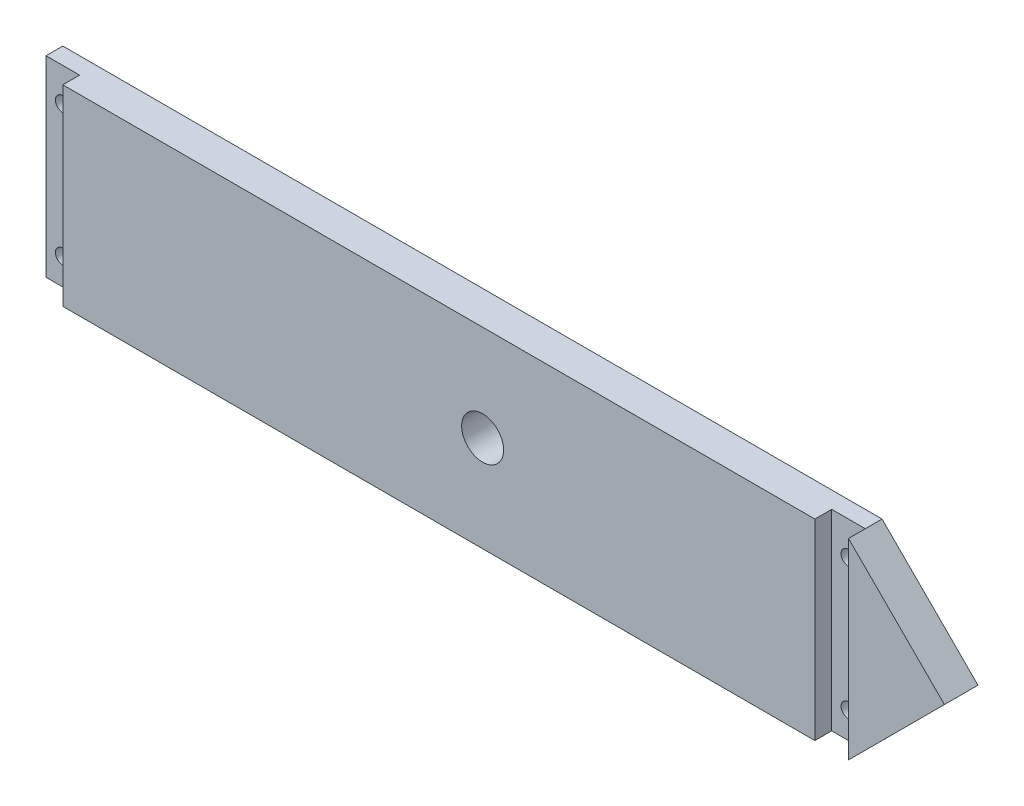
SolidWorks part; units mm, degrees
material "Brass"
ref_plane "Front Plane" through (0, 0, 0) normal (0, 0, 1) x (1, 0, 0)
ref_plane "Top Plane" through (0, 0, 0) normal (0, 1, 0) x (1, 0, 0)
ref_plane "Right Plane" through (0, 0, 0) normal (1, 0, 0) x (0, 0, -1)
sketch "Sketch1" plane through (0, 0, 0) normal (0, 0, 1) x (1, 0, 0)
  line L0 (86.5187, 18.1394) -> (-86.5187, -18.1394) construction
  line L1 (86.5187, 18.1394) -> (-86.5187, 18.1394)
  line L2 (86.5187, 18.1394) -> (86.5187, -18.1394)
  line L3 (86.5187, -18.1394) -> (-86.5187, -18.1394)
  line L4 (-86.5187, 18.1394) -> (-86.5187, -18.1394)
  line L5 (0, 67.5638) -> (0, -55.9908) construction
  line L6 (-104.9725, 0) -> (100.2455, 0) construction
  dimension "sight arm length" = 173.0375
  dimension "D2" = 36.2788
extrude "Extrude2" add sketch "Sketch1" along normal blind 6.35
sketch "Sketch8" plane through (0, 0, 6.35) normal (0, 0, 1) x (1, 0, 0)
  line L0 (-0.7937, -951.8707) -> (-0.7937, 49048.1293) construction
  line L1 (-80.1687, -1000.1415) -> (-80.1687, 48999.8585) construction
  line L2 (62.0306, -999.8068) -> (62.0306, 49000.1932) construction
  line L3 (68.3806, -999.1373) -> (68.3806, 49000.8627) construction
  line L5 (-86.5187, 18.1394) -> (-80.1687, 18.1394)
  line L6 (-80.1687, 18.1394) -> (-80.1687, -18.1394)
  line L8 (-80.1687, -18.1394) -> (-86.5187, -18.1394)
  line L9 (-86.5187, -18.1394) -> (-86.5187, 18.1394)
  line L10 (62.0306, 18.1394) -> (68.3806, 18.1394)
  line L11 (86.5187, 18.1394) -> (-86.5187, 18.1394) construction
  line L12 (68.3806, 18.1394) -> (68.3806, -18.1394)
  line L13 (68.3806, -18.1394) -> (62.0306, -18.1394)
  line L14 (-86.5187, -18.1394) -> (86.5187, -18.1394) construction
  line L15 (62.0306, -18.1394) -> (62.0306, 18.1394)
  line L17 (86.5187, -18.1394) -> (86.5187, 18.1394) construction
  dimension "D1" = 6.35
  dimension "D2" = 6.35
  dimension "D3" = 18.1381
  dimension "D4" = 173.0375
  dimension "D5" = 62.8244
  dimension "D6" = 79.375
extrude "Extrude7" cut sketch "Sketch8" against normal blind 3.175
sketch "Sketch18" plane through (0, 0, 6.35) normal (0, 0, 1) x (1, 0, 0)
  line L0 (86.5188, -1000) -> (86.5187, 49000) construction
  line L1 (86.5187, -18.1394) -> (86.5187, 18.1394) construction
  line L2 (68.3806, -1000) -> (68.3806, 49000) construction
  line L3 (68.3806, -18.1394) -> (68.3806, 18.1394) construction
  line L4 (86.5187, 0) -> (-35267.5826, 35356.5768) construction
  line L5 (86.5187, 0) -> (-35267.5826, -35356.5768) construction
  line L6 (86.5187, 0) -> (-35267.5826, 35356.5768) construction
  line L7 (113.5192, -985.2417) -> (113.5192, 49014.7583) construction
  line L8 (86.5188, 0) -> (68.3806, 18.1394)
  line L9 (68.3806, 18.1394) -> (113.5192, 18.1394)
  line L10 (86.5188, 0) -> (68.3806, -18.1394)
  line L11 (113.5192, -18.1394) -> (113.5192, 18.1394)
  line L12 (113.5192, -18.1394) -> (68.3806, -18.1394)
  point P5 (86.5187, 0)
  point P10 (68.3806, 0)
extrude "Extrude8" cut sketch "Sketch18" against normal through all
sketch "Sketch19" plane through (0, 0, 6.35) normal (0, 0, 1) x (1, 0, 0)
  line L0 (-80.1687, -18.1394) -> (62.0306, -18.1394) construction
  line L1 (-86.5187, 18.1394) -> (-86.5187, -18.1394) construction
  circle A0 centre (-0.7937, 0) radius 3.9688
  point P2 (-9.0691, -18.1394)
  dimension "D3" = 7.9375
  dimension "D1" = 18.1394
  dimension "D2" = 85.725
extrude "Extrude9" cut sketch "Sketch19" against normal through all
hole_wizard "CSK for #3 Flat Head Socket Cap Screw1" positions "Sketch20" profile "Sketch21" countersink size "#3" standard "Ansi Inch" end condition through all
sketch "Sketch20" plane through (2.3819, -14.071, 0) normal (0, 0, -1) x (-1, 0, 0)
  point P0 (-62.8237, 25.8604)
  point P1 (-62.8237, 0.8922)
sketch "Sketch21" plane through (65.2056, 11.7894, 0) normal (1, 0, 0) x (0, 1, 0)
  line L0 (0, 0) -> (0, 6.35)
  line L1 (0, 6.35) -> (1.397, 6.35)
  line L2 (1.397, 6.35) -> (1.397, 1.5662)
  line L3 (1.397, 1.5662) -> (2.7584, 0)
  line L5 (2.7584, 0) -> (0, 0)
  line L6 (-1.397, 1.5662) -> (-2.7584, 0) construction
  line L11 (0, -6.35) -> (0, 107.95) construction
  dimension "Thru Hole Dia." = 2.794
  dimension "Thru Hole Depth" = 6.35
  dimension "Near C'Sink Dia." = 5.5169
  dimension "Near C'Sink Angle" = 82
hole_wizard "CSK for #3 Flat Head Socket Cap Screw2" positions "Sketch22" profile "Sketch23" countersink size "#3" standard "Ansi Inch" end condition through all
sketch "Sketch22" plane through (2.3819, -14.071, 0) normal (0, 0, -1) x (-1, 0, 0)
  point P0 (85.7256, 25.8604)
  point P1 (85.7256, 0.8922)
sketch "Sketch23" plane through (-83.3438, 11.7894, 0) normal (1, 0, 0) x (0, 1, 0)
  line L0 (0, 0) -> (0, 6.35)
  line L1 (0, 6.35) -> (1.397, 6.35)
  line L2 (1.397, 6.35) -> (1.397, 1.5662)
  line L3 (1.397, 1.5662) -> (2.7584, 0)
  line L5 (2.7584, 0) -> (0, 0)
  line L6 (-1.397, 1.5662) -> (-2.7584, 0) construction
  line L11 (0, -6.35) -> (0, 107.95) construction
  dimension "Thru Hole Dia." = 2.794
  dimension "Thru Hole Depth" = 6.35
  dimension "Near C'Sink Dia." = 5.5169
  dimension "Near C'Sink Angle" = 82
